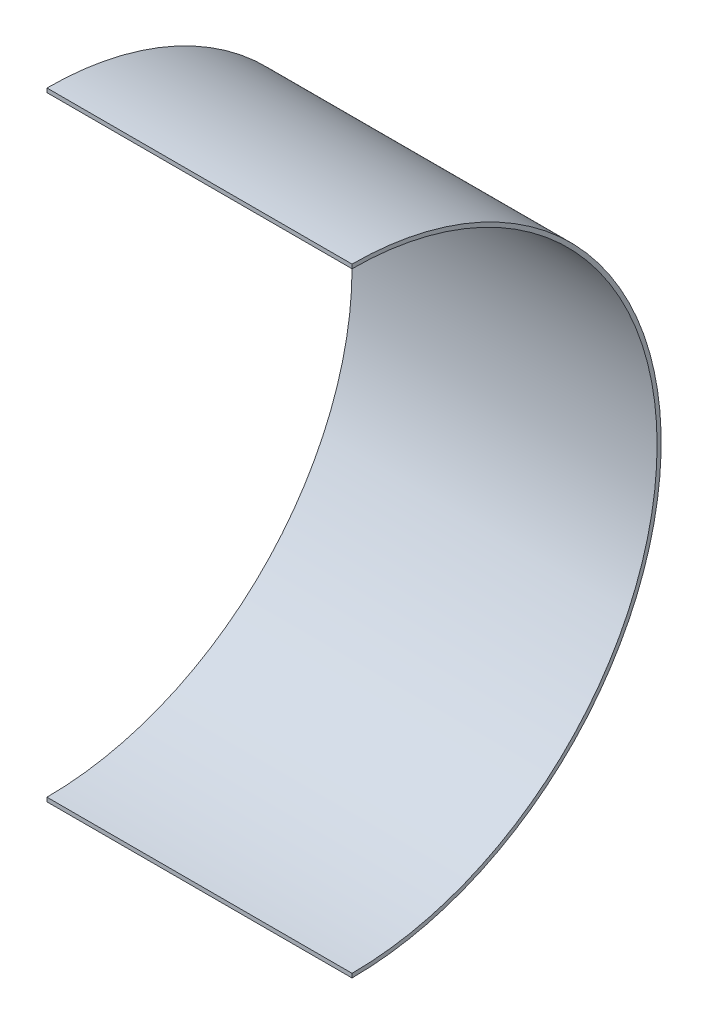
SolidWorks part; units mm, degrees
ref_plane "Front Plane" through (0, 0, 0) normal (0, 0, 1) x (1, 0, 0)
ref_plane "Top Plane" through (0, 0, 0) normal (0, 1, 0) x (1, 0, 0)
ref_plane "Right Plane" through (0, 0, 0) normal (1, 0, 0) x (0, 0, -1)
sketch "Sketch1" plane through (0, 0, 0) normal (1, 0, 0) x (0, 0, -1)
  line L0 (0, 190.5) -> (0, -190.5) construction
  line L1 (0, 190.5) -> (0, 0) construction
  line L2 (190.5, 0) -> (190.5, 190.5) construction
  line L3 (0, 190.5) -> (190.5, 190.5) construction
  line L4 (190.5, 0) -> (0, 190.5) construction
  arc A0 (0, -190.5) -> (0, 190.5) centre (0, 0) ccw
  dimension "D1" = 381
  dimension "D2" = 45
extrude "Extrude-Thin1" add sketch "Sketch1" along normal blind 190.5 thin
